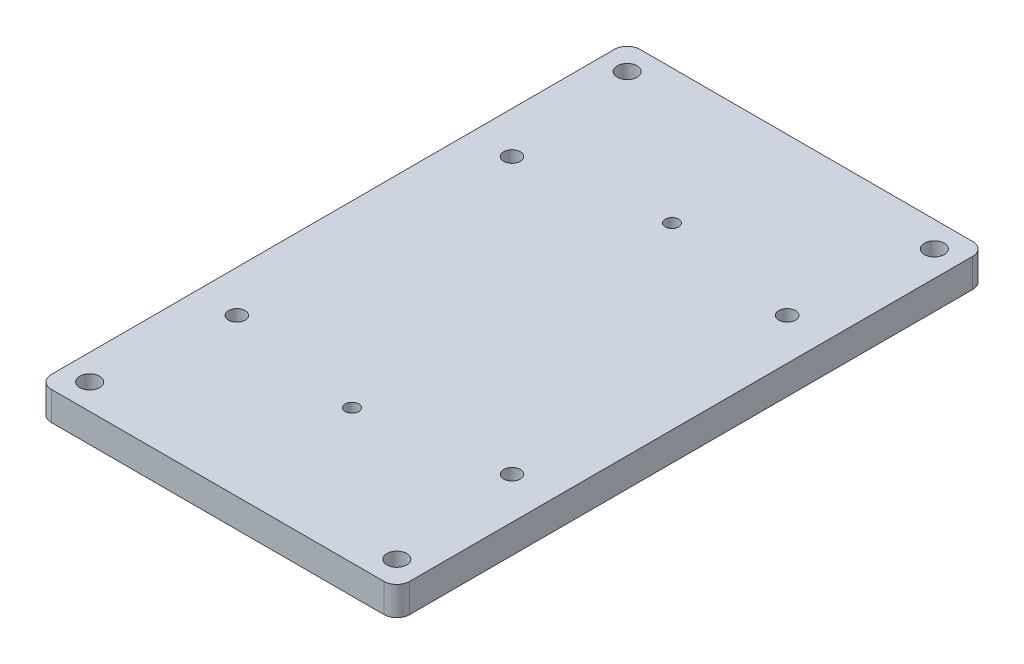
SolidWorks part; units mm, degrees
ref_plane "Front Plane" through (0, 0, 0) normal (0, 0, 1) x (1, 0, 0)
ref_plane "Top Plane" through (0, 0, 0) normal (0, 1, 0) x (1, 0, 0)
ref_plane "Right Plane" through (0, 0, 0) normal (1, 0, 0) x (0, 0, -1)
sketch "Sketch1" plane through (0, 0, 0) normal (0, 1, 0) x (1, 0, 0)
  line L0 (0, 0) -> (2.2663, 0) construction
  line L1 (0, -0.1889) -> (0, 2.4551) construction
  line L3 (-26, -46) -> (26, -46)
  line L4 (-28, -44) -> (-28, 44)
  line L5 (-26, 46) -> (26, 46)
  line L7 (-28, -46) -> (22.1425, 36.377) construction
  line L8 (-28, 46) -> (26.1335, -42.9336) construction
  line L13 (28, -44) -> (28, 44)
  line L15 (-17, -28) -> (17, -28) construction
  line L16 (-28, -17) -> (-28, 17) construction
  line L17 (-17, 28) -> (17, 28) construction
  line L18 (28, -17) -> (28, 17) construction
  line L19 (-28, -28) -> (28, 28) construction
  line L20 (-28, 28) -> (28, -28) construction
  circle A1 centre (24, 42) radius 1.55
  circle A2 centre (24, -42) radius 1.55
  circle A4 centre (-24, 42) radius 1.55
  circle A6 centre (-24, -42) radius 1.55
  arc A8 (28, 44) -> (26, 46) centre (26, 44) ccw
  arc A9 (26, -46) -> (28, -44) centre (26, -44) ccw
  arc A10 (-28, -44) -> (-26, -46) centre (-26, -44) ccw
  arc A11 (-28, 44) -> (-26, 46) centre (-26, 44) cw
  circle A14 centre (-21.5, 21.5) radius 1.3
  circle A15 centre (21.5, 21.5) radius 1.3
  circle A16 centre (21.5, -21.5) radius 1.3
  circle A17 centre (-21.5, -21.5) radius 1.3
  circle A18 centre (0, 25) radius 1.05
  circle A19 centre (0, -25) radius 1.05
  arc A20 (17, 28) -> (28, 17) centre (17, 17) cw construction
  arc A21 (17, -28) -> (28, -17) centre (17, -17) ccw construction
  arc A22 (-17, -28) -> (-28, -17) centre (-17, -17) cw construction
  arc A23 (-28, 17) -> (-17, 28) centre (-17, 17) cw construction
  point P4 (0, 0)
  point P22 (0, 0)
  point P48 (24, 0)
  dimension "D2" = 3.1
  dimension "D3" = 56
  dimension "D5" = 42
  dimension "D9" = 2
  dimension "D12" = 21.5
  dimension "D10" = 2.6
  dimension "D11" = 21.5
  dimension "D13" = 2.1
  dimension "D14" = 25
  dimension "D15" = 11
  dimension "D4" = 92
  dimension "D6" = 24
  dimension "D7" = 56
  dimension "D8" = 56
extrude "Boss-Extrude1" add sketch "Sketch1" along normal blind 4.5
